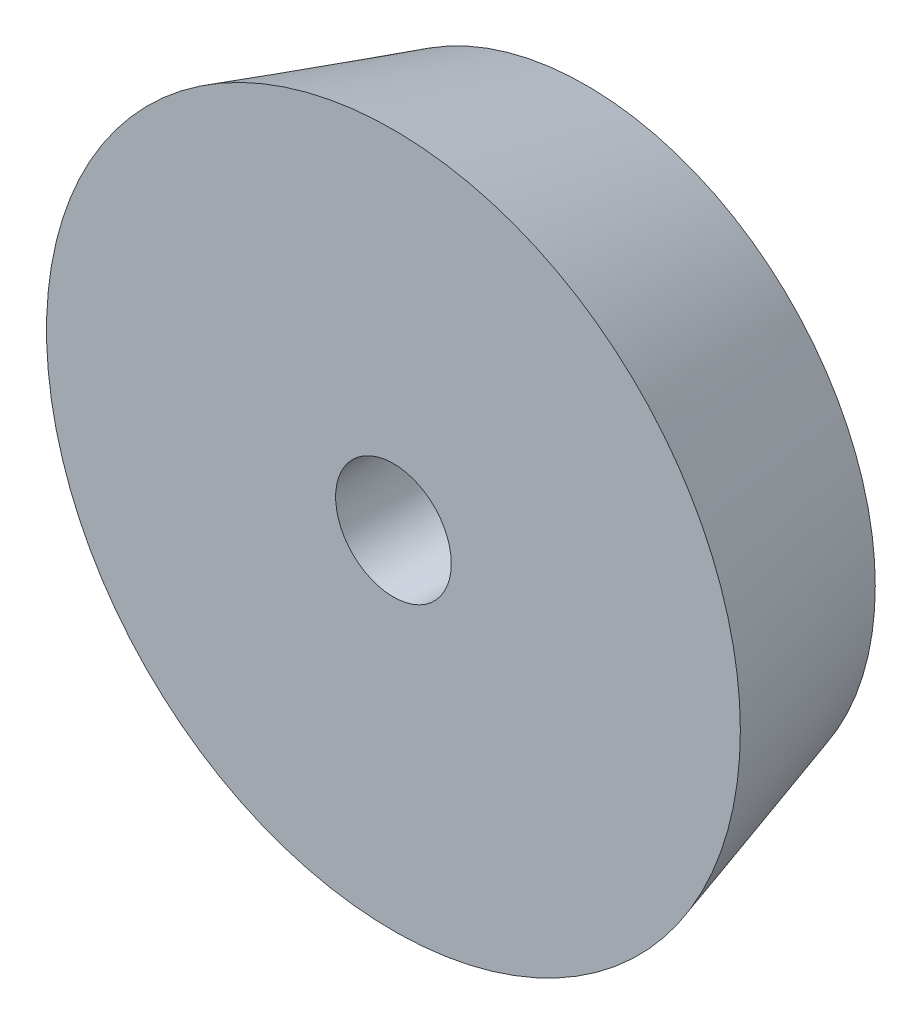
SolidWorks part; units mm, degrees
ref_plane "Front Plane" through (0, 0, 0) normal (0, 0, 1) x (1, 0, 0)
ref_plane "Top Plane" through (0, 0, 0) normal (0, 1, 0) x (1, 0, 0)
ref_plane "Right Plane" through (0, 0, 0) normal (1, 0, 0) x (0, 0, -1)
sketch "Sketch1" plane through (0, 0, 0) normal (0, 1, 0) x (1, 0, 0)
  line L0 (0, 0) -> (9, 0)
  line L1 (0, 0) -> (0, 5)
  line L2 (1.5, 0) -> (1.5, 5)
  line L3 (0, 5) -> (1.5, 5)
  line L4 (1.5, 5) -> (7.5, 5)
  line L5 (7.5, 5) -> (9, 0)
  dimension "D1" = 9
  dimension "D2" = 5
  dimension "D3" = 1.5
  dimension "D4" = 6
revolve "Revolve1" add sketch "Sketch1" angle 360 about L1
sketch "Sketch2" plane through (0, 0, -5) normal (0, 0, -1) x (-1, 0, 0)
  circle A0 centre (0, 0) radius 4.5
  dimension "D1" = 9
extrude "Cut-Extrude1" cut sketch "Sketch2" against normal blind 2
